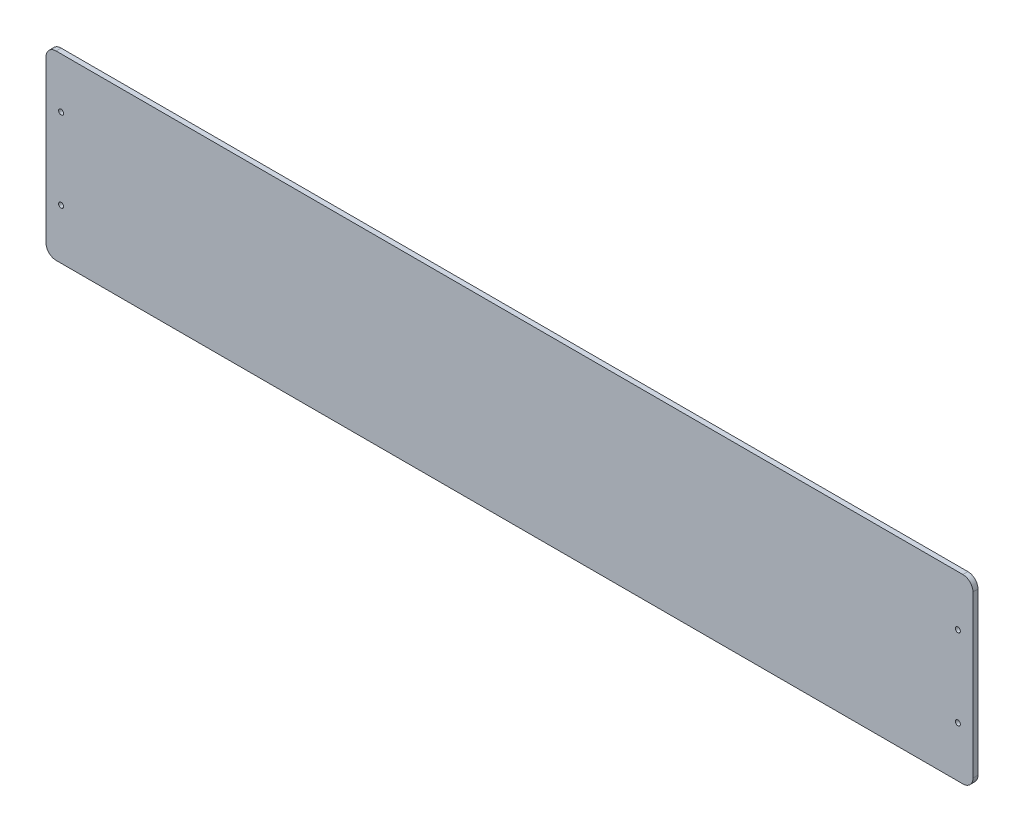
SolidWorks part; units mm, degrees
ref_plane "Alzado" through (0, 0, 0) normal (0, 0, 1) x (1, 0, 0)
ref_plane "Planta" through (0, 0, 0) normal (0, 1, 0) x (1, 0, 0)
ref_plane "Vista lateral" through (0, 0, 0) normal (1, 0, 0) x (0, 0, -1)
sketch "Croquis1" plane through (0, 0, 0) normal (0, 0, 1) x (1, 0, 0)
  line L1 (460, -90) -> (-460, -90)
  line L2 (460, -90) -> (460, 90)
  line L3 (460, 90) -> (-460, 90)
  line L4 (-460, -90) -> (-460, 90)
  line L5 (460, -90) -> (-460, 90) construction
  line L6 (460, 90) -> (-460, -90) construction
  point P0 (0, 0)
  dimension "D1" = 920
  dimension "D2" = 180
extrude "Extruir1" add sketch "Croquis1" along normal blind 5
fillet "Redondeo1" radius 10 4 edges at (460, -90, 2.5) (460, 90, 2.5) (-460, -90, 2.5) (-460, 90, 2.5)
sketch "Croquis2" plane through (0, 0, 5) normal (0, 0, 1) x (1, 0, 0)
  line L0 (445, 90) -> (445, -90) construction
  line L1 (450, 90) -> (-450, 90) construction
  line L2 (-450, -90) -> (450, -90) construction
  line L3 (460, -80) -> (460, 80) construction
  line L4 (0, 0) -> (-460, 0) construction
  line L5 (-460, 80) -> (-460, -80) construction
  line L6 (0, 0) -> (0, 90) construction
  circle A0 centre (445, 40) radius 2.5
  circle A1 centre (445, -40) radius 2.5
  circle A2 centre (-445, 40) radius 2.5
  circle A3 centre (-445, -40) radius 2.5
  dimension "D2" = 5
  dimension "D3" = 50
  dimension "D1" = 15
extrude "Extruir2" cut sketch "Croquis2" against normal blind 10
